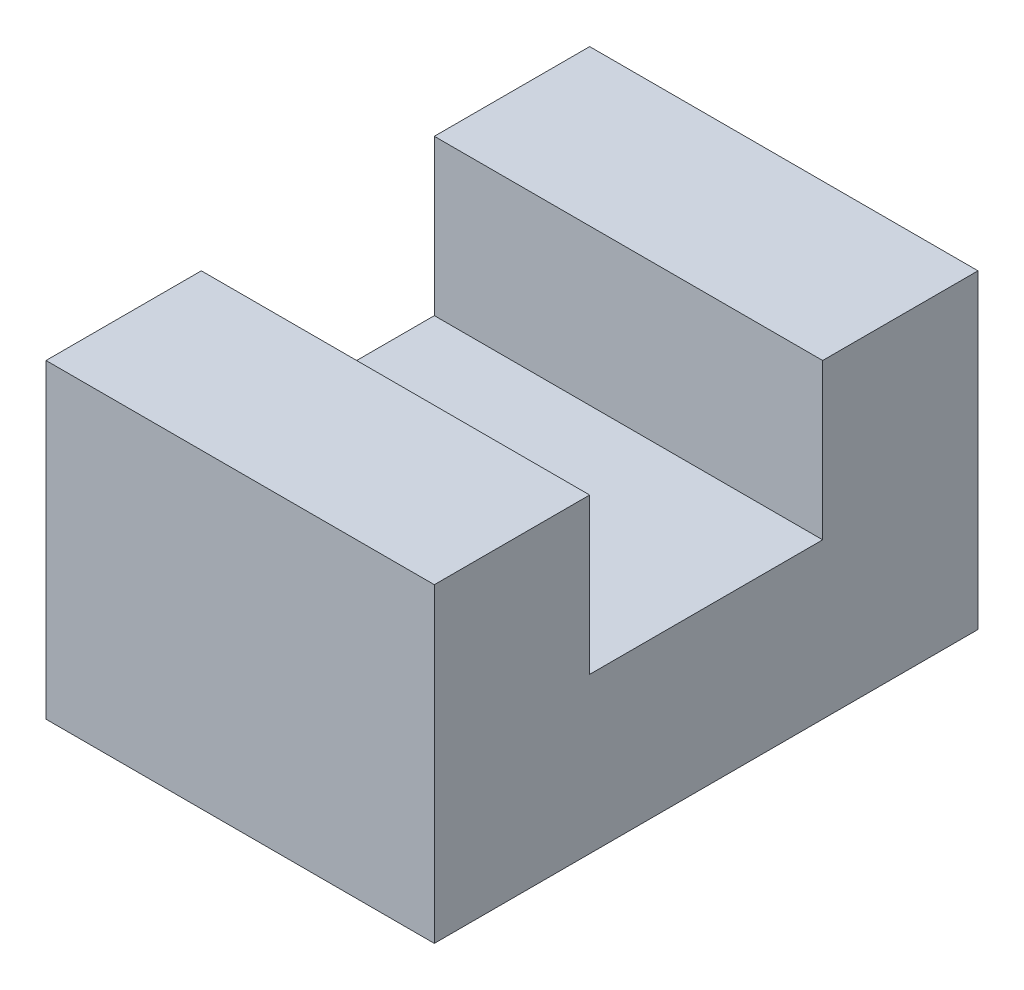
SolidWorks part; units mm, degrees
ref_plane "Front Plane" through (0, 0, 0) normal (0, 0, 1) x (1, 0, 0)
ref_plane "Top Plane" through (0, 0, 0) normal (0, 1, 0) x (1, 0, 0)
ref_plane "Right Plane" through (0, 0, 0) normal (1, 0, 0) x (0, 0, -1)
sketch "Sketch1" plane through (0, 0, 0) normal (0, 1, 0) x (1, 0, 0)
  line L1 (-10.0524, -22.6417) -> (-5.0524, -22.6417)
  line L2 (-10.0524, -22.6417) -> (-10.0524, -29.6417)
  line L3 (-10.0524, -29.6417) -> (-5.0524, -29.6417)
  line L4 (-5.0524, -22.6417) -> (-5.0524, -29.6417)
  dimension "D1" = 7
  dimension "D2" = 5
extrude "Boss-Extrude1" add sketch "Sketch1" along normal blind 2 contours L1 L4 L3 L2
sketch "Sketch2" plane through (0, 2, 0) normal (0, 1, 0) x (1, 0, 0)
  line L0 (-5.0524, -22.6417) -> (-5.0524, -29.6417) construction
  line L1 (-10.0524, -22.6417) -> (-5.0524, -22.6417)
  line L2 (-10.0524, -22.6417) -> (-10.0524, -24.6417)
  line L3 (-10.0524, -24.6417) -> (-5.0524, -24.6417)
  line L4 (-5.0524, -22.6417) -> (-5.0524, -24.6417)
  line L6 (-10.0524, -29.6417) -> (-5.0524, -29.6417)
  line L7 (-10.0524, -29.6417) -> (-10.0524, -27.6417)
  line L8 (-10.0524, -27.6417) -> (-5.0524, -27.6417)
  line L9 (-5.0524, -29.6417) -> (-5.0524, -27.6417)
  dimension "D1" = 3
extrude "Boss-Extrude2" add sketch "Sketch2" along normal blind 2
equation "\"spiralD\"= 62"
equation "\"spiralHeight\"= 5"
equation "\"spiralHoleWidth\"=2"
equation "\"spiralED\"= 58"
equation "\"spiralHoleHeight\"=3"
equation "\"axisLength\"=10"
equation "\"axisHeight\"=2"
equation "\"bitDepth\"=1"
equation "\"bitD\"=1"
equation "\"D1@Sketch1\"=\"spiralHoleWidth\"+5"
equation "\"D1@Sketch2\"=\"spiralHoleWidth\"+1"
